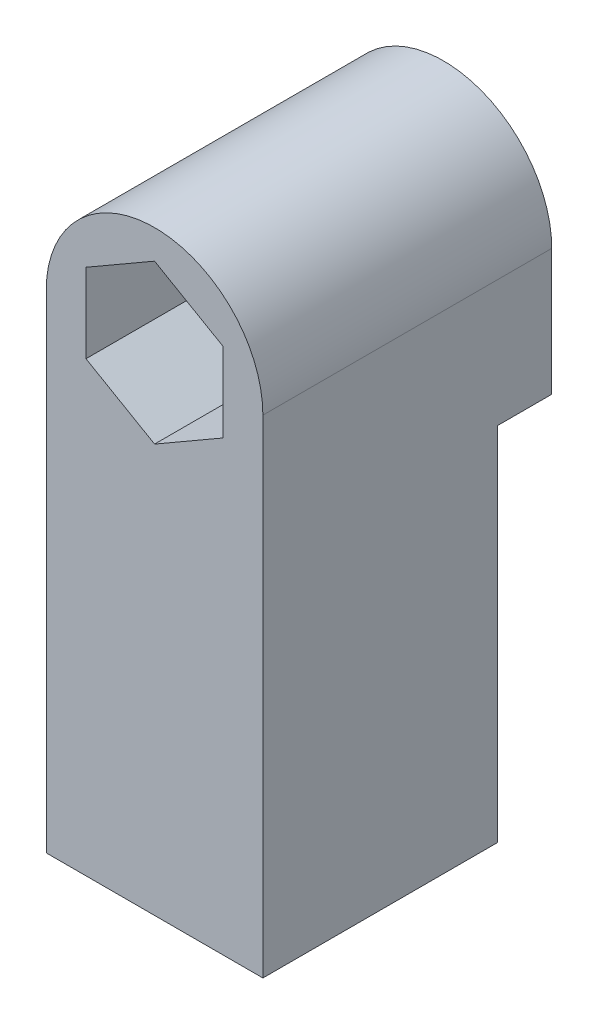
SolidWorks part; units mm, degrees
ref_plane "Plano frontal" through (0, 0, 0) normal (0, 0, 1) x (1, 0, 0)
ref_plane "Plano superior" through (0, 0, 0) normal (0, 1, 0) x (1, 0, 0)
ref_plane "Plano direito" through (0, 0, 0) normal (1, 0, 0) x (0, 0, -1)
sketch "Esboço1" plane through (0, 0, 0) normal (0, 0, 1) x (1, 0, 0)
  line L0 (-6, 0) -> (-6, -27)
  line L1 (-6, -27) -> (6, -27)
  line L2 (6, -27) -> (6, 0)
  arc A0 (6, 0) -> (-6, 0) centre (0, 0) ccw
  dimension "D1" = 12
  dimension "D2" = 27
extrude "Ressalto-extrusão1" add sketch "Esboço1" along normal blind 16
sketch "Esboço2" plane through (0, 0, 16) normal (0, 0, 1) x (1, 0, 0)
  line L1 (0, 4.3879) -> (-3.8, 2.1939)
  line L2 (-3.8, 2.1939) -> (-3.8, -2.1939)
  line L3 (-3.8, -2.1939) -> (0, -4.3879)
  line L4 (0, -4.3879) -> (3.8, -2.1939)
  line L5 (3.8, -2.1939) -> (3.8, 2.1939)
  line L6 (3.8, 2.1939) -> (0, 4.3879)
  circle A0 centre (0, 0) radius 3.8 construction
  dimension "D1" = 7.6
extrude "Corte-extrusão1" cut sketch "Esboço2" against normal through all
sketch "Esboço8" plane through (6, 0, 0) normal (1, 0, 0) x (0, 0, -1)
  line L0 (0, -27) -> (0, 0) construction
  line L1 (0, -7) -> (-3, -7)
  line L2 (0, -7) -> (0, -27)
  line L3 (0, -27) -> (-3, -27)
  line L4 (-3, -7) -> (-3, -27)
  line L5 (-16, -27) -> (0, -27) construction
  dimension "D1" = 3
  dimension "D2" = 20
extrude "Corte-extrusão4" cut sketch "Esboço8" against normal through all
sketch "Esboço5" plane through (0, -27, 0) normal (0, -1, 0) x (1, 0, 0)
  line L0 (-6, 16) -> (6, 16) construction
  line L2 (-6, 3) -> (6, 3) construction
  circle A0 centre (0, 13.5) radius 1
  circle A1 centre (0, 5.5) radius 1
  point P6 (0, 0)
  point P7 (0, 5.1498)
  dimension "D1" = 2
  dimension "D2" = 2
  dimension "D3" = 2.5
  dimension "D4" = 2.5
extrude "Corte-extrusão2" cut sketch "Esboço5" against normal blind 5
